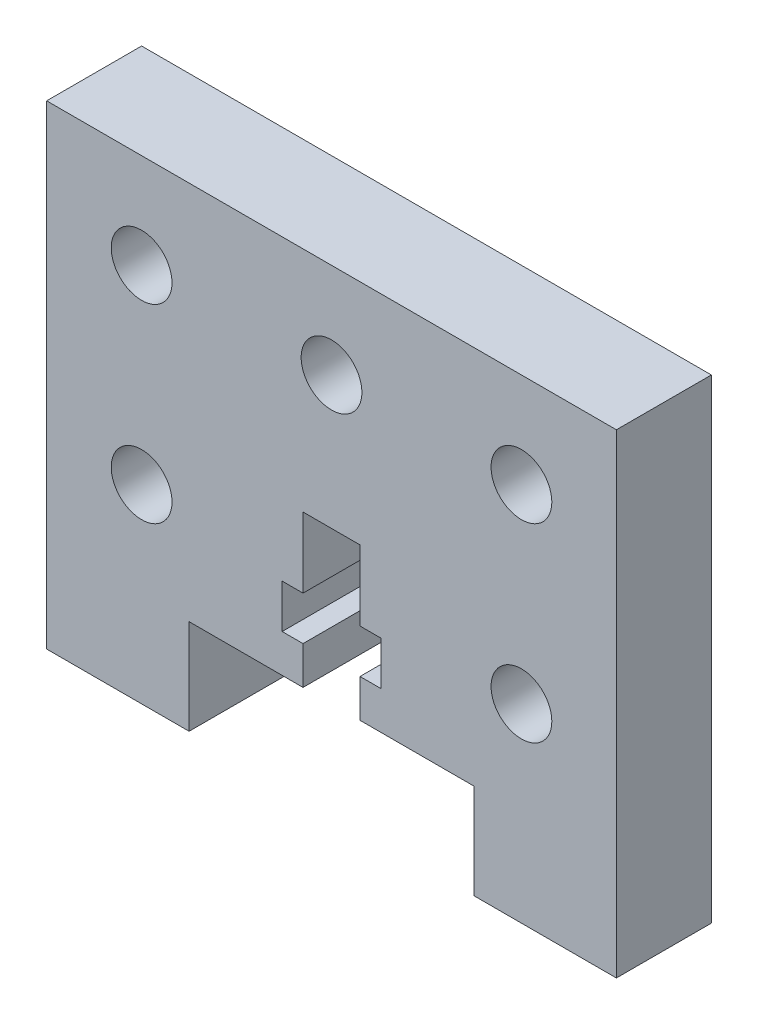
SolidWorks part; units mm, degrees
ref_plane "Plan de face" through (0, 0, 0) normal (0, 0, 1) x (1, 0, 0)
ref_plane "Plan de dessus" through (0, 0, 0) normal (0, 1, 0) x (1, 0, 0)
ref_plane "Plan de droite" through (0, 0, 0) normal (1, 0, 0) x (0, 0, -1)
sketch "Esquisse1" plane through (0, 0, 0) normal (0, 0, 1) x (1, 0, 0)
  line L0 (0, 0) -> (7.5, 0)
  line L1 (7.5, 0) -> (7.5, 5)
  line L2 (7.5, 5) -> (22.5, 5) construction
  line L3 (22.5, 5) -> (22.5, 0)
  line L4 (22.5, 0) -> (30, 0)
  line L5 (30, 0) -> (30, 25)
  line L6 (30, 25) -> (0, 25)
  line L7 (0, 25) -> (0, 0)
  line L8 (15, 25) -> (15, -15) construction
  line L9 (5, 0) -> (5, 9.3) construction
  line L10 (0, 10) -> (13.5, 10) construction
  line L11 (15, 0) -> (15, 9.3) construction
  line L12 (25, 0) -> (25, 9.3) construction
  line L13 (7.5, 5) -> (13.5, 5)
  line L14 (13.5, 5) -> (13.5, 7)
  line L15 (13.5, 7) -> (12.4, 7)
  line L16 (12.4, 7) -> (12.4, 9.3)
  line L17 (12.4, 9.3) -> (13.5, 9.3)
  line L18 (13.5, 9.3) -> (13.5, 13)
  line L19 (13.5, 13) -> (16.5, 13)
  line L20 (16.5, 13) -> (16.5, 9.3)
  line L21 (16.5, 9.3) -> (17.6, 9.3)
  line L22 (17.6, 9.3) -> (17.6, 7)
  line L23 (17.6, 7) -> (16.5, 7)
  line L24 (16.5, 7) -> (16.5, 5)
  line L25 (16.5, 5) -> (22.5, 5)
  circle A0 centre (5, 10) radius 1.6
  circle A1 centre (5, 20) radius 1.6
  circle A2 centre (25, 10) radius 1.6
  circle A3 centre (15, 20) radius 1.6
  circle A5 centre (25, 20) radius 1.6
  circle A8 centre (15, 10) radius 1.6 [skipped]
  point P42 (0, 0)
  point P44 (0, 0)
  point P45 (0, 0)
  point P46 (0, 0)
  dimension "D7" = 3.2
  dimension "D1" = 15
  dimension "D2" = 5
  dimension "D3" = 30
  dimension "D4" = 25
  dimension "D5" = 5
  dimension "D6" = 10
  dimension "D11" = 3
  dimension "D12" = 5.2
  dimension "D13" = 2.3
  dimension "D14" = 2
  dimension "D15" = 8
  dimension "D8" = 2
  dimension "D9" = 3
  dimension "D10" = 3
extrude "Boss.-Extru.1" add sketch "Esquisse1" along normal blind 5
